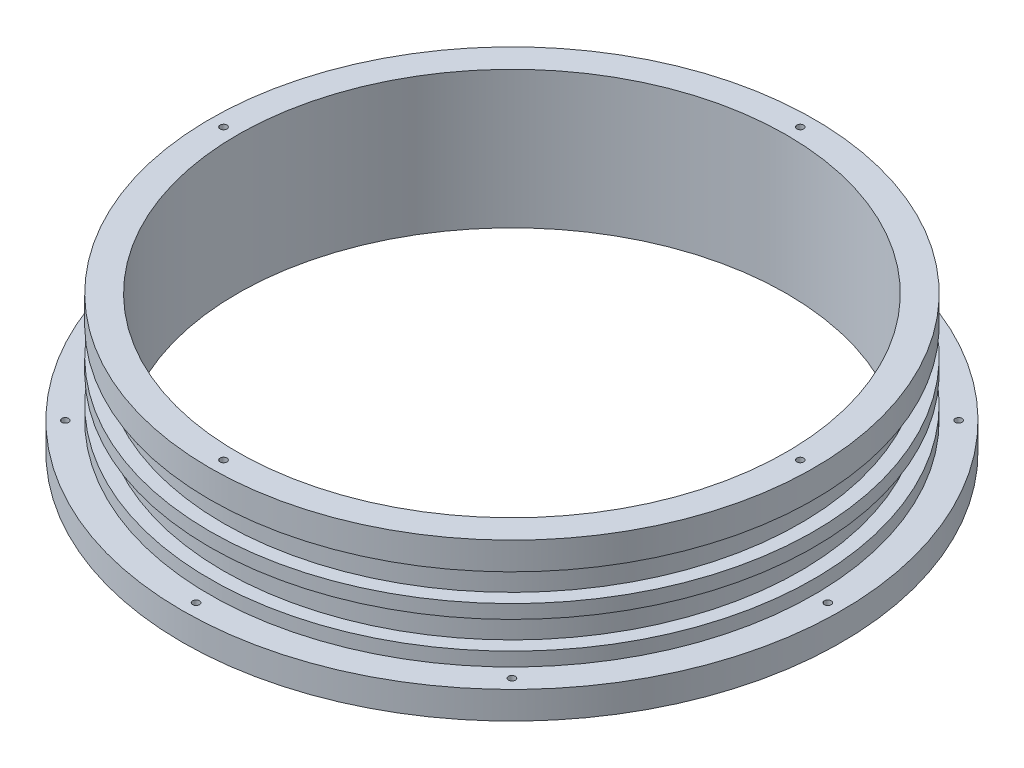
SolidWorks part; units mm, degrees
material "6061 Alloy"
ref_plane "Front Plane" through (0, 0, 0) normal (0, 0, 1) x (1, 0, 0)
ref_plane "Top Plane" through (0, 0, 0) normal (0, 1, 0) x (1, 0, 0)
ref_plane "Right Plane" through (0, 0, 0) normal (1, 0, 0) x (0, 0, -1)
sketch "Sketch2" plane through (0, 0, 0) normal (0, 1, 0) x (1, 0, 0)
  circle A0 centre (0, 0) radius 76.2
extrude "Boss-Extrude1" add sketch "Sketch2" along normal blind 6.35
sketch "Sketch3" plane through (0, 0, 0) normal (0, 1, 0) x (1, 0, 0)
  circle A0 centre (0, 0) radius 69.85
extrude "Boss-Extrude2" add sketch "Sketch3" along normal blind 9.525
sketch "Sketch4" plane through (0, 0, 0) normal (0, 1, 0) x (1, 0, 0)
  circle A0 centre (0, 0) radius 66.675
extrude "Boss-Extrude3" add sketch "Sketch4" along normal blind 15.875
sketch "Sketch6" plane through (0, 15.875, 0) normal (0, 1, 0) x (1, 0, 0)
  circle A0 centre (0, 0) radius 69.85
extrude "Boss-Extrude4" add sketch "Sketch6" along normal blind 3.175
sketch "Sketch7" plane through (0, 19.05, 0) normal (0, 1, 0) x (1, 0, 0)
  circle A0 centre (0, 0) radius 66.675
extrude "Boss-Extrude5" add sketch "Sketch7" along normal blind 6.35
sketch "Sketch8" plane through (0, 25.4, 0) normal (0, 1, 0) x (1, 0, 0)
  circle A0 centre (0, 0) radius 69.85
extrude "Boss-Extrude6" add sketch "Sketch8" along normal blind 6.35
sketch "Sketch9" plane through (0, 0, 0) normal (0, -1, 0) x (1, 0, 0)
  circle A0 centre (0, 0) radius 63.5
extrude "Cut-Extrude1" cut sketch "Sketch9" against normal through all
sketch "Sketch10" plane through (0, 6.35, 0) normal (0, 1, 0) x (1, 0, 0)
  circle A0 centre (0, 73.025) radius 0.7937
  circle A1 centre (51.6365, 51.6365) radius 0.7937
  circle A2 centre (73.025, 0) radius 0.7937
  circle A3 centre (51.6365, -51.6365) radius 0.7937
  circle A4 centre (0, -73.025) radius 0.7937
  circle A5 centre (-51.6365, -51.6365) radius 0.7937
  circle A6 centre (-73.025, 0) radius 0.7937
  circle A7 centre (-51.6365, 51.6365) radius 0.7937
  point P19 (0, 0)
  dimension "D1" = 8
extrude "Cut-Extrude2" cut sketch "Sketch10" against normal through all
sketch "Sketch11" plane through (0, 0, 0) normal (0, -1, 0) x (1, 0, 0)
  circle A0 centre (0, 0) radius 66.675
  circle A1 centre (0, 0) radius 69.85
extrude "Cut-Extrude3" cut sketch "Sketch11" against normal blind 3.175
sketch "Sketch12" plane through (0, 31.75, 0) normal (0, 1, 0) x (1, 0, 0)
  circle A0 centre (0, 66.675) radius 0.7937
  circle A1 centre (66.675, 0) radius 0.7938
  circle A2 centre (0, -66.675) radius 0.7938
  circle A3 centre (-66.675, 0) radius 0.7938
  point P11 (0, 0)
  dimension "D1" = 4
extrude "Cut-Extrude4" cut sketch "Sketch12" against normal blind 3.175
